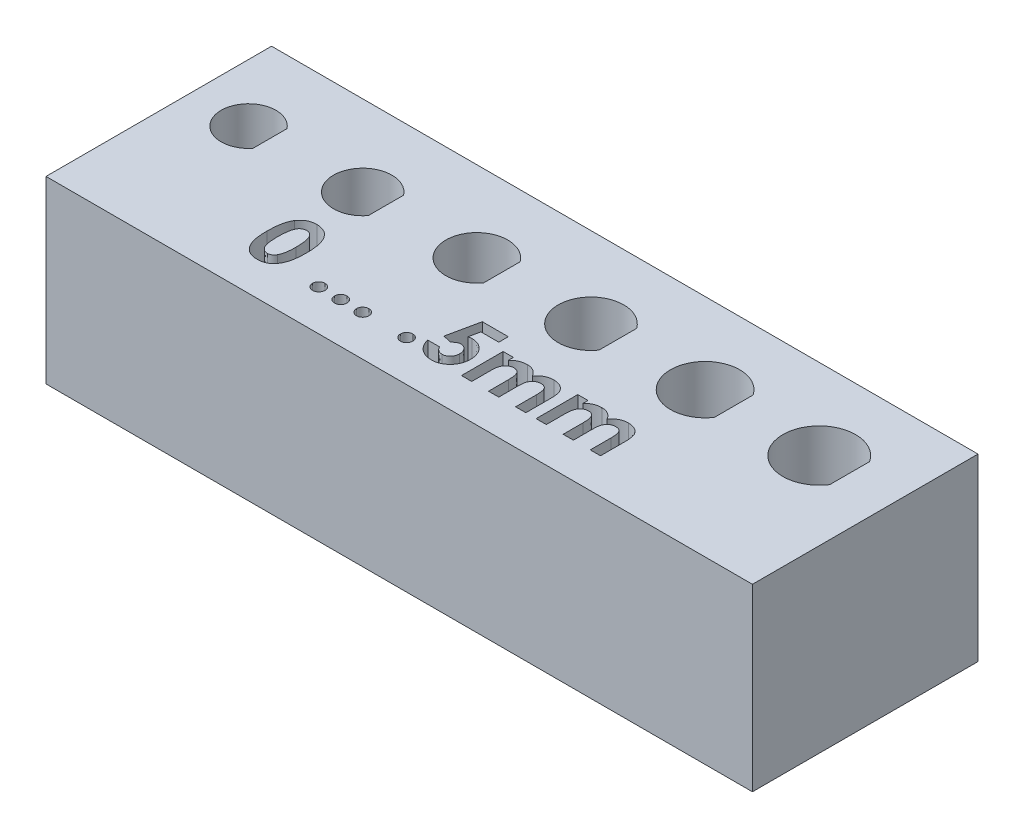
SolidWorks part; units mm, degrees
ref_plane "Front Plane" through (0, 0, 0) normal (0, 0, 1) x (1, 0, 0)
ref_plane "Top Plane" through (0, 0, 0) normal (0, 1, 0) x (1, 0, 0)
ref_plane "Right Plane" through (0, 0, 0) normal (1, 0, 0) x (0, 0, -1)
sketch "Sketch1" plane through (0, 0, 0) normal (0, 1, 0) x (1, 0, 0)
  line L0 (1.1939, 0.9472) -> (1.1939, -0.9472) construction
  line L1 (7.5439, 0.9472) -> (7.5439, -0.9472) construction
  line L2 (13.8939, 0.9472) -> (13.8939, -0.9472) construction
  line L3 (20.2439, 0.9472) -> (20.2439, -0.9472) construction
  line L4 (26.5939, 0.9472) -> (26.5939, -0.9472) construction
  line L5 (1.1939, 0.9472) -> (1.1939, -0.9472)
  line L6 (14.0939, 1.0145) -> (14.0939, -1.0145)
  line L7 (7.6439, 0.9815) -> (7.6439, -0.9815)
  line L8 (20.5439, 1.0466) -> (20.5439, -1.0466)
  line L9 (26.9939, 1.0777) -> (26.9939, -1.0777)
  line L10 (32.9439, 0.9472) -> (32.9439, -0.9472) construction
  line L11 (33.4439, 1.1079) -> (33.4439, -1.1079)
  line L13 (-3.2099, -8.0602) -> (36.0943, -8.0602)
  line L14 (-3.2099, -8.0602) -> (-3.2099, 4.4888)
  line L15 (-3.2099, 4.4888) -> (36.0943, 4.4888)
  line L16 (36.0943, -8.0602) -> (36.0943, 4.4888)
  arc A0 (1.1939, -0.9472) -> (1.1939, 0.9472) centre (0, 0) cw construction
  arc A1 (7.5439, -0.9472) -> (7.5439, 0.9472) centre (6.35, 0) cw construction
  arc A2 (13.8939, -0.9472) -> (13.8939, 0.9472) centre (12.7, 0) cw construction
  arc A3 (20.2439, -0.9472) -> (20.2439, 0.9472) centre (19.05, 0) cw construction
  arc A4 (26.5939, -0.9472) -> (26.5939, 0.9472) centre (25.4, 0) cw construction
  arc A5 (1.1939, -0.9472) -> (1.1939, 0.9472) centre (0, 0) cw
  arc A6 (14.0939, -1.0145) -> (14.0939, 1.0145) centre (12.7, 0) cw
  arc A7 (7.6439, -0.9815) -> (7.6439, 0.9815) centre (6.35, 0) cw
  arc A8 (20.5439, -1.0466) -> (20.5439, 1.0466) centre (19.05, 0) cw
  arc A9 (26.9939, -1.0777) -> (26.9939, 1.0777) centre (25.4, 0) cw
  arc A10 (32.9439, -0.9472) -> (32.9439, 0.9472) centre (31.75, 0) cw construction
  arc A11 (33.4439, -1.1079) -> (33.4439, 1.1079) centre (31.75, 0) cw
  point P4 (1.1939, 0)
  point P5 (-1.524, 0)
  point P11 (7.5439, 0)
  point P12 (4.826, 0)
  point P16 (13.8939, 0)
  point P17 (11.176, 0)
  point P21 (20.2439, 0)
  point P22 (17.526, 0)
  point P26 (26.5939, 0)
  point P27 (23.876, 0)
  point P45 (32.9439, 0)
  point P46 (30.226, 0)
  dimension "D1" = 1.524
  dimension "D2" = 2.7179
  dimension "D4" = 0
  dimension "D5" = 0.2
  dimension "D6" = 0.1
  dimension "D7" = 0.3
  dimension "D8" = 0.4
  dimension "D9" = 0.5
  dimension "D3" = 6
extrude "Boss-Extrude1" add sketch "Sketch1" along normal blind 10
sketch "Sketch2" plane through (0, 10, 0) normal (0, 1, 0) x (1, 0, 0)
  text T0 "<b>0 ... .5mm</b>"
extrude "Cut-Extrude1" cut sketch "Sketch2" against normal blind 2.5
